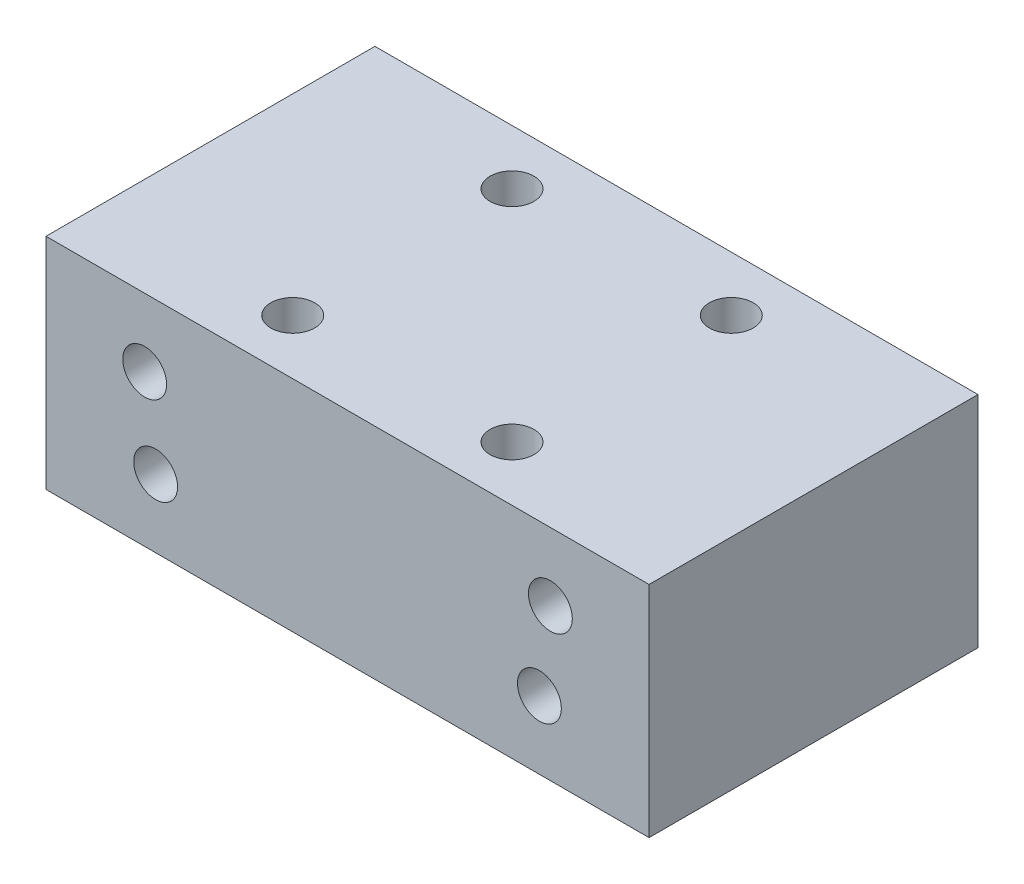
SolidWorks part; units mm, degrees
ref_plane "Front Plane" through (0, 0, 0) normal (0, 0, 1) x (1, 0, 0)
ref_plane "Top Plane" through (0, 0, 0) normal (0, 1, 0) x (1, 0, 0)
ref_plane "Right Plane" through (0, 0, 0) normal (1, 0, 0) x (0, 0, -1)
sketch "Sketch1" plane through (0, 0, 0) normal (0, 0, 1) x (1, 0, 0)
  line L1 (-69.85, 25.4) -> (69.85, 25.4)
  line L2 (-69.85, 25.4) -> (-69.85, -25.4)
  line L3 (-69.85, -25.4) -> (69.85, -25.4)
  line L4 (69.85, 25.4) -> (69.85, -25.4)
  line L5 (-69.85, 25.4) -> (69.85, -25.4) construction
  line L6 (-69.85, -25.4) -> (69.85, 25.4) construction
  point P0 (0, 0)
  dimension "D1" = 139.7
  dimension "D2" = 50.8
extrude "Boss-Extrude1" add sketch "Sketch1" along normal mid plane 76.2
sketch "Sketch2" plane through (0, 0, 38.1) normal (0, 0, 1) x (1, 0, 0)
  line L1 (69.85, -25.4) -> (44.45, -25.4)
  line L2 (69.85, -25.4) -> (69.85, -9.652)
  line L3 (69.85, -9.652) -> (44.45, -9.652)
  line L4 (44.45, -25.4) -> (44.45, -9.652)
  line L5 (69.85, -25.4) -> (46.99, -25.4)
  line L6 (69.85, -25.4) -> (69.85, 9.652)
  line L7 (69.85, 9.652) -> (46.99, 9.652)
  line L8 (46.99, -25.4) -> (46.99, 9.652)
  dimension "D1" = 15.748
  dimension "D2" = 25.4
  dimension "D3" = 22.86
  dimension "D4" = 35.052
hole_wizard "0.4in Diameter Hole zaxis" positions "Sketch3" profile "Sketch4" hole size "#97" standard "ANSI Inch" end condition through all
sketch "Sketch3" plane through (0, 0, 38.1) normal (0, 0, 1) x (1, 0, 0)
  point P0 (46.99, 9.652)
  point P3 (44.45, -9.652)
sketch "Sketch4" plane through (46.99, 9.652, 38.1) normal (1, 0, 0) x (0, -1, 0)
  line L0 (0, 0) -> (0, 76.2)
  line L1 (0, 76.2) -> (5.08, 76.2)
  line L2 (5.08, 76.2) -> (5.08, 0)
  line L5 (5.08, 0) -> (0, 0)
  line L11 (0, -6.35) -> (0, 107.95) construction
  dimension "Thru Hole Dia." = 10.16
  dimension "Thru Hole Depth" = 76.2
mirror "Mirror1" about plane through (0, 0, 0) normal (1, 0, 0) of "0.4in Diameter Hole zaxis"
sketch "Sketch5" plane through (0, 25.4, 0) normal (0, 1, 0) x (1, 0, 0)
  line L1 (25.4, -25.4) -> (-25.4, -25.4)
  line L2 (25.4, -25.4) -> (25.4, 25.4)
  line L3 (25.4, 25.4) -> (-25.4, 25.4)
  line L4 (-25.4, -25.4) -> (-25.4, 25.4)
  line L5 (25.4, -25.4) -> (-25.4, 25.4) construction
  line L6 (25.4, 25.4) -> (-25.4, -25.4) construction
  point P0 (0, 0)
  dimension "D1" = 50.8
  dimension "D2" = 50.8
hole_wizard "0.4in Diameter Hole yaxis" positions "Sketch6" profile "Sketch7" hole size "#97" standard "ANSI Inch" end condition through all
sketch "Sketch6" plane through (0, 25.4, 0) normal (0, 1, 0) x (1, 0, 0)
  point P0 (-25.4, 25.4)
  point P3 (-25.4, -25.4)
  point P6 (25.4, -25.4)
  point P12 (25.4, 25.4)
sketch "Sketch7" plane through (-25.4, 25.4, -25.4) normal (1, 0, 0) x (0, 0, 1)
  line L0 (0, 0) -> (0, 50.8)
  line L1 (0, 50.8) -> (5.08, 50.8)
  line L2 (5.08, 50.8) -> (5.08, 0)
  line L5 (5.08, 0) -> (0, 0)
  line L11 (0, -6.35) -> (0, 107.95) construction
  dimension "Thru Hole Dia." = 10.16
  dimension "Thru Hole Depth" = 50.8
